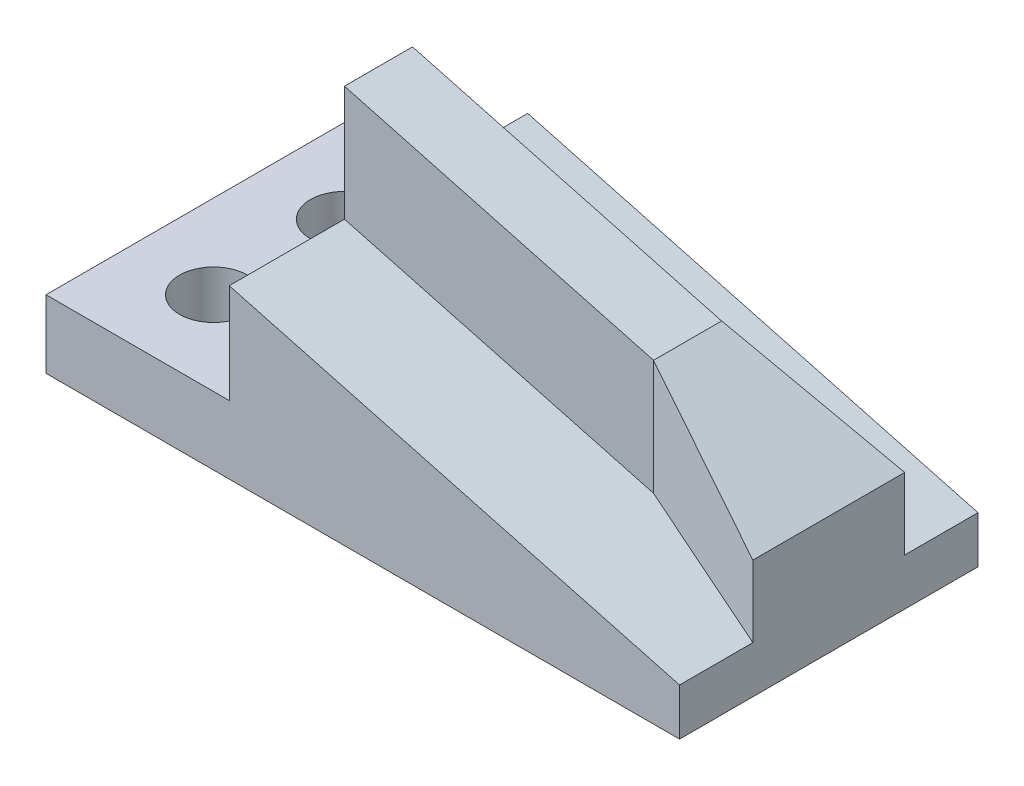
SolidWorks part; units mm, degrees
ref_plane "Front Plane" through (0, 0, 0) normal (0, 0, 1) x (1, 0, 0)
ref_plane "Top Plane" through (0, 0, 0) normal (0, 1, 0) x (1, 0, 0)
ref_plane "Right Plane" through (0, 0, 0) normal (1, 0, 0) x (0, 0, -1)
sketch "Sketch1" plane through (0, 0, 0) normal (0, 1, 0) x (1, 0, 0)
  line L1 (-60.5, 28.5) -> (60.5, 28.5)
  line L2 (-60.5, 28.5) -> (-60.5, -28.5)
  line L3 (-60.5, -28.5) -> (60.5, -28.5)
  line L4 (60.5, 28.5) -> (60.5, -28.5)
  line L5 (-60.5, 28.5) -> (60.5, -28.5) construction
  line L6 (-60.5, -28.5) -> (60.5, 28.5) construction
  point P0 (0, 0)
  dimension "D1" = 57
  dimension "D2" = 121
extrude "Boss-Extrude1" add sketch "Sketch1" along normal blind 13
sketch "Sketch3" plane through (0, 0, 28.5) normal (0, 0, 1) x (1, 0, 0)
  line L0 (-60.5, 13) -> (60.5, 13) construction
  line L1 (-25.5, 13) -> (60.5, 13)
  line L2 (-25.5, 13) -> (-25.5, 54)
  line L3 (-25.5, 54) -> (60.5, 54)
  line L4 (60.5, 13) -> (60.5, 54)
  line L5 (60.5, 13) -> (60.5, 0) construction
  line L6 (-60.5, 0) -> (60.5, 0) construction
  line L7 (-60.5, 13) -> (-60.5, 0) construction
  dimension "D1" = 54
  dimension "D2" = 35
extrude "Boss-Extrude2" add sketch "Sketch3" against normal up to surface (57 mm away) up to face at (0, 6.5, -28.5)
sketch "Sketch5" plane through (0, 54, 0) normal (0, 1, 0) x (1, 0, 0)
  line L0 (-30.5257, 0) -> (63.873, 0) construction
  line L2 (-25.5, 28.5) -> (-25.5, -28.5) construction
  line L3 (-25.5, -6.5) -> (33.5, -6.5)
  line L4 (33.5, -6.5) -> (60.5, -14.5)
  line L5 (60.5, 28.5) -> (60.5, -28.5) construction
  line L6 (33.5, 6.5) -> (60.5, 14.5)
  line L7 (-25.5, 6.5) -> (33.5, 6.5)
  line L9 (-25.5, -6.5) -> (-25.5, -28.5)
  line L10 (-25.5, -28.5) -> (60.5, -28.5)
  line L11 (60.5, -28.5) -> (60.5, -14.5)
  line L12 (-25.5, 6.5) -> (-25.5, 28.5)
  line L13 (-25.5, 28.5) -> (60.5, 28.5)
  line L14 (60.5, 28.5) -> (60.5, 14.5)
  point P14 (-25.5, 0)
  dimension "D1" = 27
  dimension "D2" = 13
  dimension "D3" = 29
extrude "Cut-Extrude1" cut sketch "Sketch5" against normal up to surface (41 mm away) up to face at (-43, 13, 0)
sketch "Sketch6" plane through (0, 0, 28.5) normal (0, 0, 1) x (1, 0, 0)
  line L0 (-25.5, 32) -> (60.5, 8.9564)
  line L2 (-25.5, 13) -> (-25.5, 54) construction
  line L3 (-25.5, 0) -> (-25.5, 54) construction
  line L4 (-60.5, 0) -> (60.5, 0) construction
  line L5 (-60.5, 13) -> (-60.5, 0) construction
  line L6 (-25.5, 32) -> (-25.5, 13)
  line L7 (-60.5, 13) -> (60.5, 13) construction
  line L8 (-25.5, 32) -> (20.0417, 32) construction
  line L9 (60.5, 13) -> (60.5, 0) construction
  line L10 (-25.5, 13) -> (60.5, 8.9564)
  dimension "D1" = 35
  dimension "D2" = 54
  dimension "D3" = 22
  dimension "D4" = 15
extrude "Boss-Extrude3" add sketch "Sketch6" against normal through all
sketch "Sketch7" plane through (0, 0, 28.5) normal (0, 0, 1) x (1, 0, 0)
  line L0 (-25.5, 54) -> (62.3866, 54) construction
  line L1 (-60.5, 0) -> (60.5, 0) construction
  line L2 (-25.5, 0) -> (-25.5, 54) construction
  line L3 (-60.5, 13) -> (-60.5, 0) construction
  line L5 (-25.5, 54) -> (33.5368, 38.1811)
  line L6 (33.5368, 38.1811) -> (60.5, 22.6139)
  line L7 (33.5368, 38.1811) -> (64.2662, 38.1811) construction
  line L9 (60.5, 0) -> (60.5, 67.8491) construction
  line L10 (-25.5, 54) -> (60.5, 54)
  line L11 (60.5, 54) -> (60.5, 22.6139)
  dimension "D1" = 35
  dimension "D2" = 15
  dimension "D3" = 30
  dimension "D4" = 54
extrude "Cut-Extrude3" cut sketch "Sketch7" against normal through all
sketch "Sketch8" plane through (0, 0, 28.5) normal (0, 0, 1) x (1, 0, 0)
  line L0 (45.409, 13) -> (60.5, 13)
  line L1 (45.409, 13) -> (60.5, 13) construction
  line L2 (45.409, 13) -> (60.5, 13) construction
  line L3 (60.5, 13) -> (60.5, 8.9564)
  line L4 (60.5, 13) -> (60.5, 0) construction
  line L5 (60.5, 8.9564) -> (45.409, 13)
  line L6 (45.409, 13) -> (-25.5, 32) construction
extrude "Cut-Extrude4" cut sketch "Sketch8" against normal up to surface (14 mm away)
sketch "Sketch9" plane through (0, 0, -28.5) normal (0, 0, -1) x (-1, 0, 0)
  line L0 (-45.409, 13) -> (-60.5, 13)
  line L1 (-60.5, 13) -> (-60.5, 8.9564)
  line L2 (-60.5, 13) -> (-60.5, 0) construction
  line L3 (-60.5, 8.9564) -> (-45.409, 13)
  line L4 (-45.409, 13) -> (-33.5, 16.191) construction
extrude "Cut-Extrude5" cut sketch "Sketch9" against normal up to surface (14 mm away)
sketch "Sketch10" plane through (0, 13, 0) normal (0, 1, 0) x (1, 0, 0)
  line L0 (-60.5, -28.5) -> (-25.5, -28.5) construction
  line L1 (-60.5, 28.5) -> (-60.5, -28.5) construction
  circle A0 centre (-44.5, 12.5) radius 6.5
  circle A1 centre (-44.5, -12.5) radius 6.5
  dimension "D4" = 13
  dimension "D1" = 25
  dimension "D2" = 16
  dimension "D3" = 16
extrude "Cut-Extrude6" cut sketch "Sketch10" against normal through all
